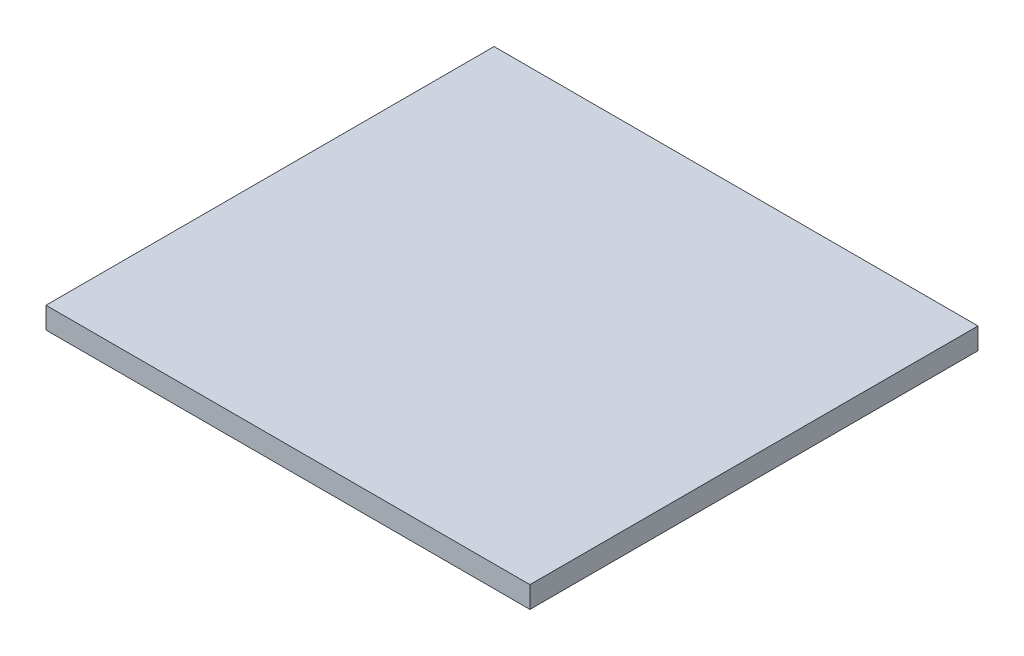
SolidWorks part; units mm, degrees
ref_plane "Alzado" through (0, 0, 0) normal (0, 0, 1) x (1, 0, 0)
ref_plane "Planta" through (0, 0, 0) normal (0, 1, 0) x (1, 0, 0)
ref_plane "Vista lateral" through (0, 0, 0) normal (1, 0, 0) x (0, 0, -1)
ref_plane "Plano_DobsonBaseMovil" through (0, 32, 0) normal (0, 1, 0) x (1, 0, 0)
sketch "SkDobsonBaseMovil" plane through (0, 32, 0) normal (0, 1, 0) x (1, 0, 0)
  line L1 (-202.5, -187.5) -> (202.5, -187.5)
  line L2 (-202.5, -187.5) -> (-202.5, 187.5)
  line L3 (-202.5, 187.5) -> (202.5, 187.5)
  line L4 (202.5, -187.5) -> (202.5, 187.5)
extrude "DobsonBaseMovil" add sketch "SkDobsonBaseMovil" along normal blind 18 separate body
